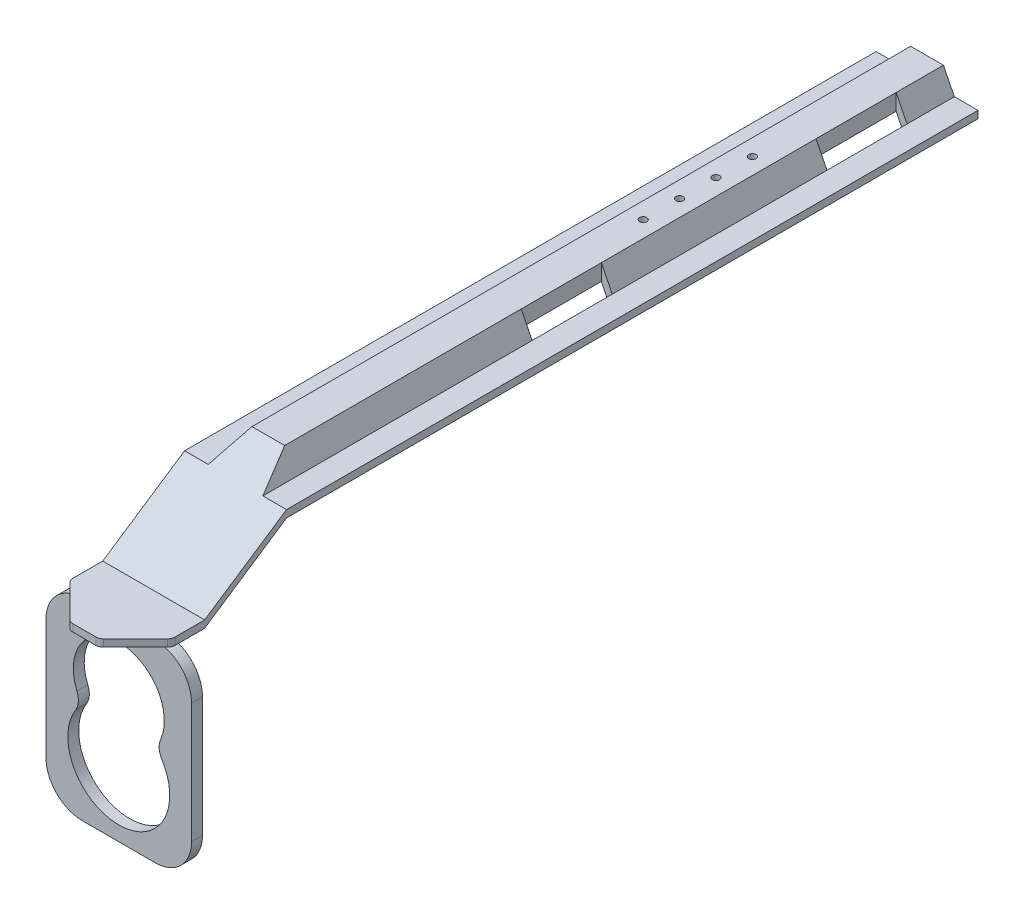
SolidWorks part; units mm, degrees
ref_plane "Front Plane" through (0, 0, 0) normal (0, 0, 1) x (1, 0, 0)
ref_plane "Top Plane" through (0, 0, 0) normal (0, 1, 0) x (1, 0, 0)
ref_plane "Right Plane" through (0, 0, 0) normal (1, 0, 0) x (0, 0, -1)
sketch "Sketch2" plane through (0, 0, 0) normal (0, 0, 1) x (1, 0, 0)
  line L0 (-14, -0.387) -> (-6.264, -0.387)
  line L1 (-14, -0.387) -> (-14, 1.613)
  line L3 (-4.4998, 7.613) -> (4.4998, 7.613)
  line L8 (-14, 1.613) -> (-7.5, 1.613)
  line L9 (-7.5, 1.613) -> (-4.4998, 7.613)
  line L11 (-3.2637, 5.613) -> (3.2637, 5.613)
  line L13 (-3.2637, 5.613) -> (-6.264, -0.387)
  line L14 (3.2637, 5.613) -> (6.264, -0.387)
  line L15 (-5.2639, 1.613) -> (-3.2637, 5.613) construction
  line L16 (7.5, 1.613) -> (4.4998, 7.613)
  line L17 (14, 1.613) -> (7.5, 1.613)
  line L18 (-5.2639, 1.613) -> (12, 1.613) construction
  line L19 (6.5983, 2.2173) -> (3.598, 5.613) construction
  line L21 (-14, -0.387) -> (14, -0.387) construction
  line L22 (0, 9.6464) -> (0, -4.275) construction
  line L23 (-4.4998, 7.613) -> (4.4998, 7.613) construction
  line L24 (-3.2637, 5.613) -> (3.598, 5.613) construction
  line L25 (14, -0.387) -> (14, 4.2173) construction
  line L26 (14, 4.2173) -> (7.5, 4.2173) construction
  line L27 (7.5, 4.2173) -> (4.4998, 7.613) construction
  line L28 (12, 2.2173) -> (6.5983, 2.2173) construction
  line L29 (12, 1.613) -> (12, 2.2173) construction
  line L30 (-5.2639, 1.613) -> (-5.2639, 1.613) construction
  line L31 (-5.2639, 1.613) -> (-5.2639, 1.613) construction
  line L32 (14, -0.387) -> (14, 1.613)
  line L33 (14, -0.387) -> (6.264, -0.387)
  point P4 (0, 0)
  point P10 (0, 7.613)
  point P24 (0, 7.613)
  point P25 (0, 5.613)
  point P26 (0, 7.613)
  dimension "D1" = 8
  dimension "D2" = 14
  dimension "D3" = 4.4998
  dimension "D4" = 6.5
  dimension "D5" = 2
  dimension "D6" = 2
extrude "Boss-Extrude1" add sketch "Sketch2" along normal blind 190
sketch "Sketch3" plane through (0, 7.613, 0) normal (0, 1, 0) x (1, 0, 0)
  line L0 (0, 30.3141) -> (0, -203.9263) construction
  circle A0 centre (0, -48) radius 1
  circle A1 centre (0, -58) radius 1
  circle A2 centre (0, -68) radius 1
  circle A3 centre (0, -78) radius 1
  dimension "D1" = 2
  dimension "D3" = 2
  dimension "D4" = 10
  dimension "D5" = 2
  dimension "D6" = 2
  dimension "D7" = 10
  dimension "D8" = 10
  dimension "D2" = 48
extrude "Cut-Extrude1" cut sketch "Sketch3" against normal through all
sketch "Sketch4" plane through (0, 7.613, 0) normal (0, 1, 0) x (1, 0, 0)
  line L0 (-7.5, -190) -> (-7.5, 0) construction
  line L1 (-7.5, -13) -> (-4.4998, -13)
  line L2 (-7.5, -13) -> (-7.5, -35)
  line L3 (-7.5, -35) -> (-4.4998, -35)
  line L4 (-4.4998, -13) -> (-4.4998, -35)
  line L5 (-4.4998, -190) -> (-4.4998, 0) construction
  line L6 (0, 37.8759) -> (0, -222.1241) construction
  line L7 (-7.5, -94) -> (-4.4998, -94)
  line L8 (-7.5, -94) -> (-7.5, -116)
  line L9 (-7.5, -116) -> (-4.4998, -116)
  line L10 (-4.4998, -94) -> (-4.4998, -116)
  line L11 (7.5, -116) -> (4.4998, -116)
  line L12 (4.4998, -94) -> (4.4998, -116)
  line L13 (7.5, -94) -> (4.4998, -94)
  line L14 (7.5, -94) -> (7.5, -116)
  line L15 (7.5, -35) -> (4.4998, -35)
  line L16 (4.4998, -13) -> (4.4998, -35)
  line L17 (7.5, -13) -> (4.4998, -13)
  line L18 (7.5, -13) -> (7.5, -35)
  dimension "D1" = 13
  dimension "D2" = 22
  dimension "D3" = 22
  dimension "D4" = 94
extrude "Cut-Extrude2" cut sketch "Sketch4" against normal through all
sketch "Sketch5" plane through (0, 0, 0) normal (1, 0, 0) x (0, 0, -1)
  line L0 (-116, 3.1411) -> (-116, 7.613) construction
  line L2 (-231.5, -15.387) -> (-212.5, -15.387)
  line L3 (-231.5, -13.387) -> (-212.5, -13.387)
  line L4 (-212.5, -13.387) -> (-190, 1.613)
  line L6 (-231.5, -13.387) -> (-231.5, -15.387)
  line L8 (-211.8944, -15.387) -> (-188.8906, -0.0511) construction
  line L9 (-190, -0.387) -> (-212.5, -15.387)
  line L10 (-231.5, -15.387) -> (-211.8944, -15.387) construction
  line L11 (-190, 1.613) -> (-181, 7.613)
  line L12 (-190, -0.387) -> (-178, 7.613)
  line L14 (-181, 7.613) -> (-178, 7.613)
  line L16 (-190, 7.613) -> (-116, 7.613) construction
  line L18 (-190, -0.387) -> (0, -0.387) construction
  dimension "D1" = 115.5
  dimension "D2" = 19
  dimension "D3" = 15
  dimension "D4" = 2
extrude "Boss-Extrude2" add sketch "Sketch5" along normal through all and the other way through all
chamfer "Chamfer1" distance 10 angle 45 2 edges at (-14, -14.387, 231.5) (14, -14.387, 231.5)
fillet "Fillet1" radius 2 4 edges at (-14, -14.387, 221.5) (-4, -14.387, 231.5) (14, -14.387, 221.5) (4, -14.387, 231.5)
sketch "Sketch7" plane through (0, 0, 231.5) normal (0, 0, 1) x (1, 0, 0)
  line L0 (0, -11.6515) -> (0, -83.8469) construction
  line L1 (3.1716, -15.387) -> (-3.1716, -15.387) construction
  line L6 (-10, -68.387) -> (10, -68.387)
  line L7 (-20, -58.387) -> (-20, -25.387)
  line L8 (-10, -15.387) -> (10, -15.387)
  line L9 (20, -58.387) -> (20, -25.387)
  line L12 (-20, -68.387) -> (20, -15.387) construction
  line L13 (-20, -15.387) -> (20, -68.387) construction
  arc A0 (20, -58.387) -> (10, -68.387) centre (10, -58.387) cw
  arc A1 (-10, -68.387) -> (-20, -58.387) centre (-10, -58.387) cw
  arc A2 (20, -25.387) -> (10, -15.387) centre (10, -25.387) ccw
  arc A3 (-10, -15.387) -> (-20, -25.387) centre (-10, -25.387) ccw
  arc A4 (10.1246, -40.7179) -> (-10.1246, -40.7179) centre (0, -33.387) ccw
  arc A6 (-10.1246, -40.7179) -> (10.1246, -40.7179) centre (0, -50.387) ccw
  point P3 (0, -41.887)
  point P4 (0, -41.887)
  dimension "D1" = 53
  dimension "D3" = 10
  dimension "D4" = 25
  dimension "D5" = 18
  dimension "D6" = 14
  dimension "D2" = 40
  dimension "D7" = 18
extrude "Boss-Extrude3" add sketch "Sketch7" against normal blind 12.41
sketch "Sketch8" plane through (20, 0, 0) normal (1, 0, 0) x (0, 0, -1)
  line L1 (-231.5, -68.387) -> (-222.0858, -68.387)
  line L2 (-231.5, -68.387) -> (-231.5, -15.387)
  line L3 (-231.5, -15.387) -> (-222.0858, -15.387)
  line L4 (-222.0858, -68.387) -> (-222.0858, -15.387)
extrude "Cut-Extrude3" cut sketch "Sketch8" against normal through all
sketch "Sketch9" plane through (14, 0, 0) normal (1, 0, 0) x (0, 0, -1)
  line L0 (-190, 1.613) -> (-190, 7.613)
  line L1 (-190, 7.613) -> (-181, 7.613)
  line L2 (-181, 7.613) -> (-190, 1.613)
extrude "Cut-Extrude4" cut sketch "Sketch9" against normal through all
sketch "Sketch11" plane through (0, 0, 0) normal (0, 0, -1) x (-1, 0, 0)
  line L4 (14, 7.613) -> (4.4998, 7.613)
  line L5 (4.4998, 7.613) -> (7.5, 1.613)
  line L6 (7.5, 1.613) -> (14, 1.613)
  line L7 (14, 1.613) -> (14, 7.613)
  line L8 (14, 7.613) -> (4.4998, 7.613)
  line L9 (4.4998, 7.613) -> (7.5, 1.613)
  line L10 (7.5, 1.613) -> (14, 1.613)
  line L11 (14, 1.613) -> (14, 7.613)
  line L12 (-14, 1.613) -> (-7.5, 1.613)
  line L13 (-7.5, 1.613) -> (-4.4998, 7.613)
  line L14 (-4.4998, 7.613) -> (-14, 7.613)
  line L15 (-14, 7.613) -> (-14, 1.613)
  line L16 (-14, 1.613) -> (-7.5, 1.613)
  line L17 (-7.5, 1.613) -> (-4.4998, 7.613)
  line L18 (-4.4998, 7.613) -> (-14, 7.613)
  line L19 (-14, 7.613) -> (-14, 1.613)
  dimension "D1" = 0
  dimension "D2" = 0
extrude "Cut-Extrude5" cut sketch "Sketch11" against normal through all
fillet "Fillet2" radius 5 2 edges at (-10.1246, -40.7179, 220.5879) (10.1246, -40.7179, 220.5879)
